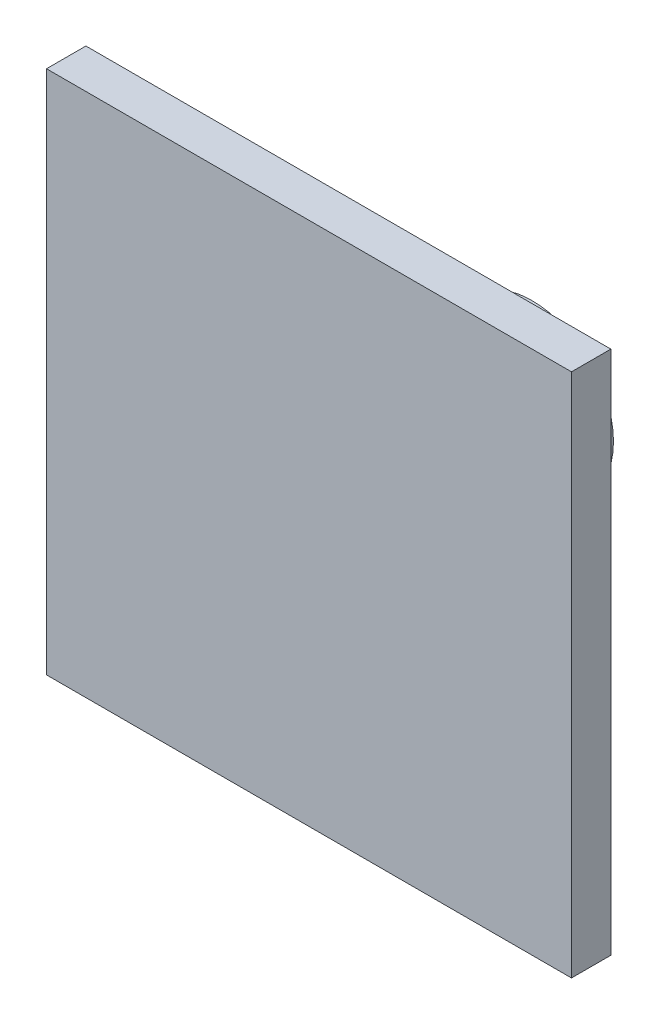
SolidWorks part; units mm, degrees
material "Сосна"
ref_plane "Front" through (0, 0, 0) normal (0, 0, 1) x (1, 0, 0)
ref_plane "Top" through (0, 0, 0) normal (0, 1, 0) x (1, 0, 0)
ref_plane "Right" through (0, 0, 0) normal (1, 0, 0) x (0, 0, -1)
sketch "Эскиз2" plane through (0, 0, 0) normal (0, 0, 1) x (1, 0, 0)
  line L1 (-10, -10) -> (10, -10)
  line L2 (-10, -10) -> (-10, 10)
  line L3 (-10, 10) -> (10, 10)
  line L4 (10, -10) -> (10, 10)
  line L5 (-10, -10) -> (10, 10) construction
  line L6 (-10, 10) -> (10, -10) construction
  point P0 (0, 0)
  dimension "D1" = 20
extrude "Основание" add sketch "Эскиз2" along normal blind 1.5
sketch "Эскиз3" plane through (0, 0, 0) normal (0, 0, 1) x (1, 0, 0)
  circle A0 centre (0, 0) radius 1.1
  circle A1 centre (0, 0) radius 3.1
  dimension "D1" = 2.2
  dimension "D2" = 2
  dimension "D3" = 6.2
extrude "Стойка" add sketch "Эскиз3" against normal blind 7
